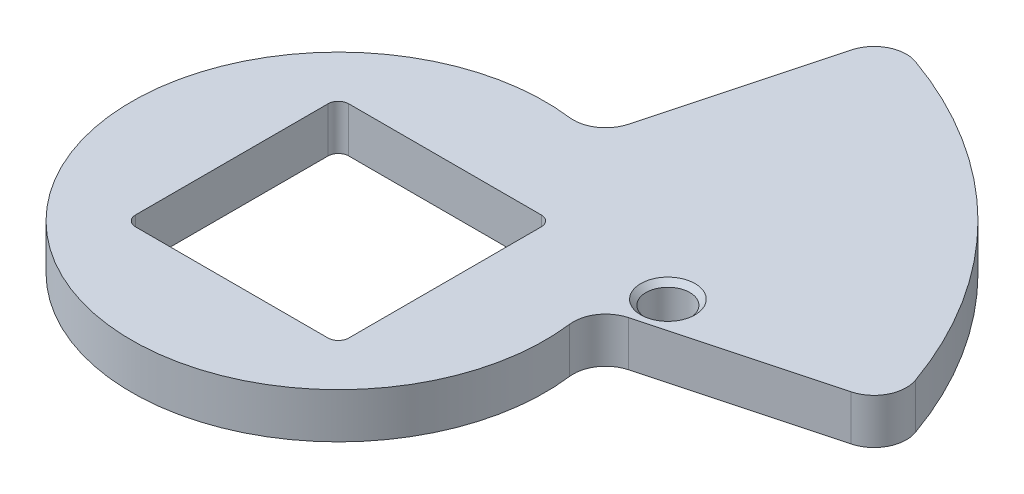
SolidWorks part; units mm, degrees
ref_plane "Front Plane" through (0, 0, 0) normal (0, 0, 1) x (1, 0, 0)
ref_plane "Top Plane" through (0, 0, 0) normal (0, 1, 0) x (1, 0, 0)
ref_plane "Right Plane" through (0, 0, 0) normal (1, 0, 0) x (0, 0, -1)
sketch "Sketch1" plane through (0, 0, 0) normal (0, 1, 0) x (1, 0, 0)
  line L0 (20.32, 0) -> (0, 0) construction
  line L1 (0, 0) -> (89.1832, 89.1832) construction
  line L2 (42.9354, 11.5045) -> (19.6276, 5.2592)
  line L3 (11.5045, 42.9354) -> (5.2592, 19.6276)
  line L4 (19.6276, 5.2592) -> (0, 0) construction
  line L5 (5.2592, 19.6276) -> (0, 0) construction
  line L7 (-10.4775, 10.4775) -> (10.4775, 10.4775)
  line L8 (-10.4775, 10.4775) -> (-10.4775, -10.4775)
  line L9 (-10.4775, -10.4775) -> (10.4775, -10.4775)
  line L10 (10.4775, 10.4775) -> (10.4775, -10.4775)
  line L11 (-10.4775, 10.4775) -> (10.4775, -10.4775) construction
  line L12 (-10.4775, -10.4775) -> (10.4775, 10.4775) construction
  arc A0 (5.2592, 19.6276) -> (19.6276, 5.2592) centre (0, 0) ccw
  arc A2 (11.5045, 42.9354) -> (42.9354, 11.5045) centre (0, 0) cw
  circle A3 centre (22.86, 9.525) radius 2.159
  dimension "D1" = 40.64
  dimension "D4" = 44.45
  dimension "D7" = 4.318
  dimension "D2" = 45
  dimension "D3" = 15
  dimension "D5" = 20.955
  dimension "D6" = 20.955
  dimension "D8" = 9.525
  dimension "D9" = 22.86
extrude "Boss-Extrude1" add sketch "Sketch1" along normal blind 4.445
fillet "Fillet1" radius 3.175 4 edges at (5.2592, 2.2225, -19.6276) (11.5045, 2.2225, -42.9354) (42.9354, 2.2225, -11.5045) (19.6276, 2.2225, -5.2592)
fillet "Fillet2" radius 1.016 4 edges at (10.4775, 2.2225, 10.4775) (-10.4775, 2.2225, 10.4775) (10.4775, 2.2225, -10.4775) (-10.4775, 2.2225, -10.4775)
chamfer "Chamfer1" distance 0.508 angle 45 2 edges at (22.86, 0, -7.366) (22.86, 4.445, -7.366)
